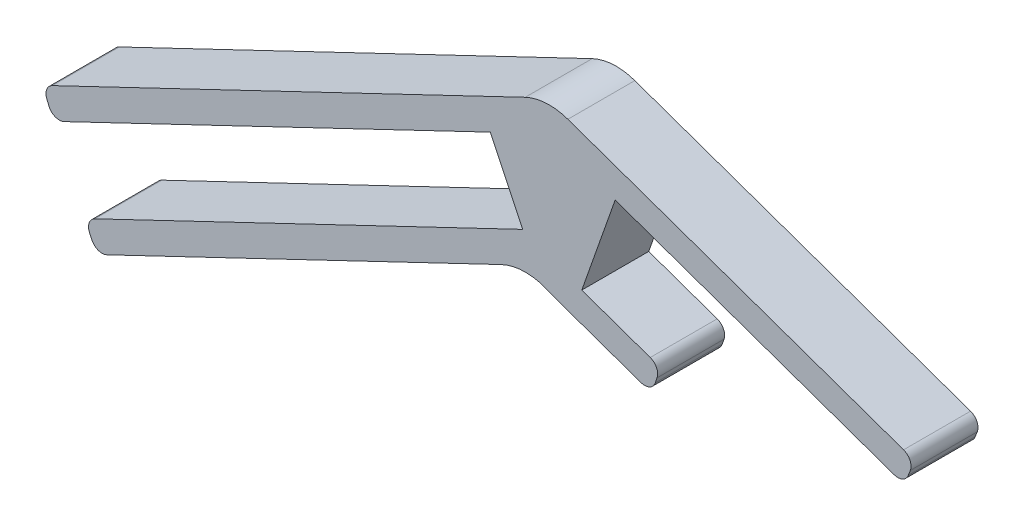
SolidWorks part; units mm, degrees
ref_plane "前基準面" through (0, 0, 0) normal (0, 0, 1) x (1, 0, 0)
ref_plane "上基準面" through (0, 0, 0) normal (0, 1, 0) x (1, 0, 0)
ref_plane "右基準面" through (0, 0, 0) normal (1, 0, 0) x (0, 0, -1)
sketch "草圖1" plane through (0, 0, 0) normal (0, 0, 1) x (1, 0, 0)
  line L0 (-89.2733, -29.9226) -> (0.9286, 13.2471)
  line L1 (0.9286, 13.2471) -> (66.9441, -10.0325)
  line L2 (13.314, 3.5778) -> (65.1382, -14.6975)
  line L4 (-87.3206, -34.5312) -> (-9.07, 2.9188)
  line L7 (-81.7177, -46.8162) -> (-3.2421, -9.2584)
  line L8 (-79.5835, -51.3379) -> (-3.2526, -14.8066)
  line L16 (7.3278, -13.3977) -> (21.474, -18.3862)
  line L17 (4.8452, -17.824) -> (19.8351, -23.11)
  line L21 (6.28, 11.36) -> (7.3566, 11.36)
  line L24 (7.3566, 11.36) -> (7.3566, 10.9804)
  line L25 (4.8452, -17.824) -> (-3.2526, -14.8066)
  line L26 (-89.2733, -29.9226) -> (-87.3206, -34.5312)
  line L27 (-81.7177, -46.8162) -> (-79.5835, -51.3379)
  line L28 (19.8351, -23.11) -> (21.474, -18.3862)
  line L29 (-3.2421, -9.2584) -> (-9.07, 2.9188)
  line L30 (7.3278, -13.3977) -> (13.314, 3.5778)
  line L31 (66.9441, -10.0325) -> (65.1382, -14.6975)
  dimension "D1" = 70
  dimension "D2" = 5
  dimension "D3" = 5
  dimension "D4" = 13.5
  dimension "D5" = 100
  dimension "D6" = 18
  dimension "D7" = 5
  dimension "D8" = 5
  dimension "D9" = 135
  dimension "D10" = 87
  dimension "D11" = 15
extrude "填料-伸長1" add sketch "草圖1" along normal blind 12
fillet "圓角1" radius 10 1 edges at (0.9286, 13.2471, 6)
fillet "圓角2" radius 10 1 edges at (-3.2526, -14.8066, 6)
fillet "圓角5" radius 2 4 edges at (19.8351, -23.11, 6) (21.474, -18.3862, 6) (65.1382, -14.6975, 6) (66.9441, -10.0325, 6)
fillet "圓角6" radius 2 4 edges at (-79.5835, -51.3379, 6) (-81.7177, -46.8162, 6) (-87.3206, -34.5312, 6) (-89.2733, -29.9226, 6)
